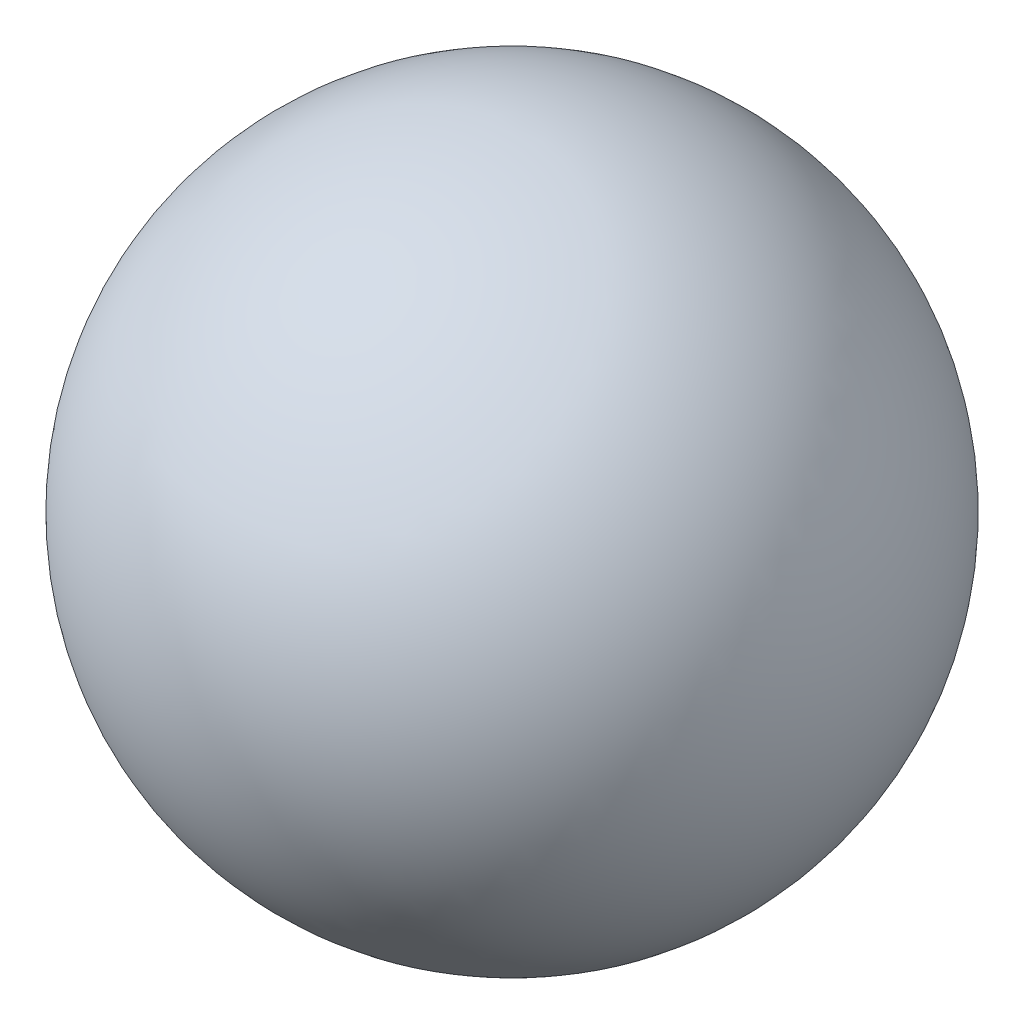
SolidWorks part; units mm, degrees
ref_plane "前视基准面" through (0, 0, 0) normal (0, 0, 1) x (1, 0, 0)
ref_plane "上视基准面" through (0, 0, 0) normal (0, 1, 0) x (1, 0, 0)
ref_plane "右视基准面" through (0, 0, 0) normal (1, 0, 0) x (0, 0, -1)
sketch "草图1" plane through (0, 0, 0) normal (0, 0, 1) x (1, 0, 0)
  line L0 (0, 90) -> (0, -90)
  circle A0 centre (0, 0) radius 90
  dimension "D1" = 180
revolve "旋转1" add sketch "草图1" angle 360 about L0
